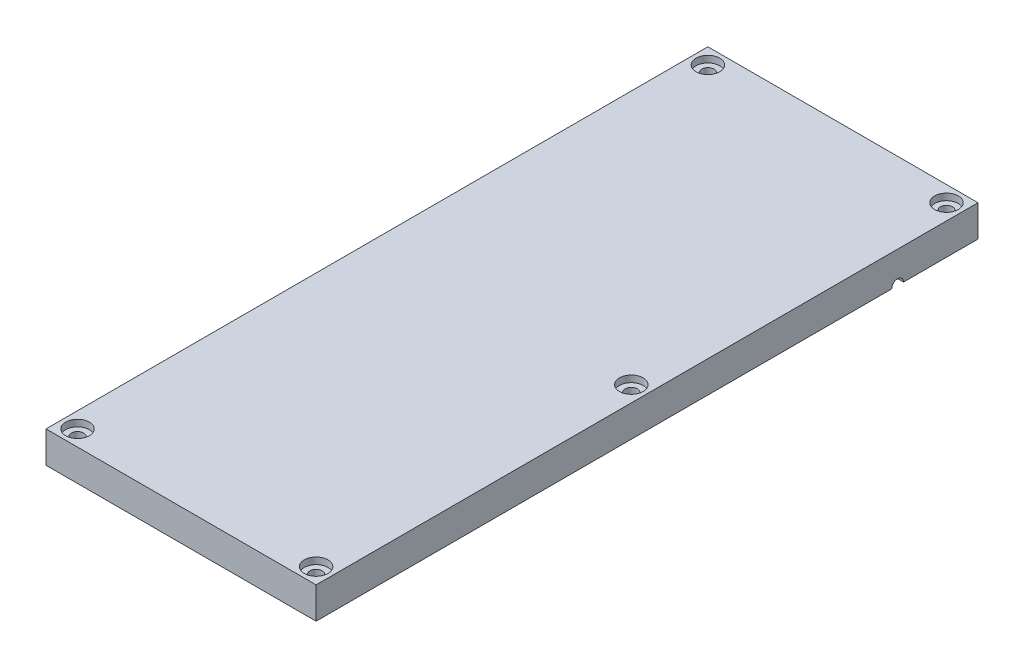
SolidWorks part; units mm, degrees
ref_plane "Front Plane" through (0, 0, 0) normal (0, 0, 1) x (1, 0, 0)
ref_plane "Top Plane" through (0, 0, 0) normal (0, 1, 0) x (1, 0, 0)
ref_plane "Right Plane" through (0, 0, 0) normal (1, 0, 0) x (0, 0, -1)
sketch "Sketch1" plane through (0, 0, 0) normal (0, 1, 0) x (1, 0, 0)
  line L1 (37.211, 0) -> (146.05, 0)
  line L2 (37.211, 0) -> (37.211, 266.7)
  line L3 (37.211, 266.7) -> (146.05, 266.7)
  line L4 (146.05, 0) -> (146.05, 266.7)
  dimension "D1" = 266.7
  dimension "D2" = 108.839
  dimension "D3" = 146.05
  dimension "D4" = 266.7
extrude "Boss-Extrude1" add sketch "Sketch1" along normal blind 12.7 from offset 12.7
hole_wizard "CBORE for #8 Binding Head Machine Screw1" positions "Sketch3" profile "Sketch2" counterbore size "#8" standard "ANSI Inch" end condition through all
sketch "Sketch3" plane through (0, 25.4, 0) normal (0, 1, 0) x (1, 0, 0)
  line L0 (146.05, 0) -> (146.05, 266.7) construction
  line L1 (37.211, 0) -> (146.05, 0) construction
  line L2 (146.05, 266.7) -> (37.211, 266.7) construction
  line L3 (37.211, 266.7) -> (37.211, 0) construction
  point P0 (139.7, 6.35)
  point P2 (139.7, 260.35)
  point P13 (43.561, 6.35)
  point P15 (43.561, 260.35)
  point P20 (139.7, 133.35)
  dimension "D1" = 6.35
  dimension "D2" = 6.35
  dimension "D3" = 6.35
  dimension "D4" = 6.35
  dimension "D5" = 6.35
  dimension "D6" = 6.35
  dimension "D7" = 6.35
  dimension "D8" = 6.35
  dimension "D9" = 6.35
  dimension "D10" = 133.35
sketch "Sketch2" plane through (139.7, 25.4, -6.35) normal (1, 0, 0) x (0, 0, 1)
  line L0 (0, 0) -> (0, 12.7)
  line L1 (0, 12.7) -> (2.4574, 12.7)
  line L3 (2.4574, 12.7) -> (2.4575, 2.667)
  line L4 (2.4575, 2.667) -> (4.7625, 2.667)
  line L5 (4.7625, 2.667) -> (4.7625, 0)
  line L7 (4.7625, 0) -> (0, 0)
  line L11 (0, -6.35) -> (0, 107.95) construction
  dimension "Thru Hole Dia." = 4.9149
  dimension "Thru Hole Depth" = 12.7
  dimension "C'Bore Dia." = 9.525
  dimension "C'Bore Depth" = 2.667
sketch "Sketch4" plane through (0, 12.7, 0) normal (0, -1, 0) x (-1, 0, 0)
  line L0 (-37.211, 266.7) -> (-37.211, 0) construction
  line L1 (-43.561, 18.415) -> (-114.935, 18.415)
  line L2 (-43.561, 18.415) -> (-43.561, 241.935)
  line L3 (-43.561, 241.935) -> (-114.935, 241.935)
  line L4 (-114.935, 18.415) -> (-114.935, 241.935)
  line L5 (-37.211, 0) -> (-146.05, 0) construction
  line L6 (-146.05, 266.7) -> (-37.211, 266.7) construction
  line L7 (-146.05, 0) -> (-146.05, 266.7) construction
  dimension "D1" = 6.35
  dimension "D2" = 18.415
  dimension "D3" = 24.765
  dimension "D4" = 31.115
extrude "Cut-Extrude1" cut sketch "Sketch4" against normal blind 9.525
sketch "Sketch5" plane through (0, 12.7, 0) normal (0, -1, 0) x (1, 0, 0)
  line L0 (114.935, -196.215) -> (120.015, -196.215)
  line L1 (114.935, -241.935) -> (114.935, -18.415) construction
  line L2 (120.015, -196.215) -> (120.015, -234.315)
  line L3 (120.015, -234.315) -> (128.905, -234.315)
  line L4 (128.905, -234.315) -> (128.905, -158.115)
  line L5 (128.905, -158.115) -> (137.795, -158.115)
  line L6 (137.795, -158.115) -> (137.795, -234.315)
  line L7 (137.795, -234.315) -> (146.05, -234.315)
  line L8 (146.05, 0) -> (146.05, -266.7) construction
  line L9 (114.935, -18.415) -> (43.561, -18.415) construction
  dimension "D1" = 38.1
  dimension "D2" = 76.2
  dimension "D3" = 76.2
  dimension "D4" = 5.08
  dimension "D5" = 8.89
  dimension "D6" = 8.89
  dimension "D7" = 177.8
sketch "Sketch6" plane through (146.05, 0, 0) normal (1, 0, 0) x (0, 0, -1)
  line L0 (234.315, 12.7) -> (158.115, 12.7) construction
  line L1 (196.215, 12.7) -> (234.315, 12.7) construction
  circle A0 centre (234.315, 12.7) radius 2.3813
  dimension "D1" = 4.7625
  dimension "D2" = 0
sweep "Cut-Sweep1" cut profiles "Sketch6" path "Sketch5"
sketch "Sketch8" plane through (0, 12.7, 0) normal (0, -1, 0) x (1, 0, 0)
  line L0 (114.935, -193.8337) -> (114.935, -18.415) construction
  line L1 (114.935, -56.515) -> (127.635, -56.515)
  line L2 (114.935, -56.515) -> (114.935, -69.215)
  line L3 (114.935, -69.215) -> (127.635, -69.215)
  line L4 (127.635, -56.515) -> (127.635, -69.215)
  line L5 (43.561, -241.935) -> (114.935, -241.935) construction
  line L6 (83.185, -241.935) -> (95.885, -241.935)
  line L7 (83.185, -241.935) -> (83.185, -254.635)
  line L8 (83.185, -254.635) -> (95.885, -254.635)
  line L9 (95.885, -241.935) -> (95.885, -254.635)
  line L10 (114.935, -241.935) -> (114.935, -18.415) construction
  line L11 (114.935, -18.415) -> (43.561, -18.415) construction
  dimension "D1" = 12.7
  dimension "D2" = 12.7
  dimension "D3" = 12.7
  dimension "D4" = 12.7
  dimension "D5" = 19.05
  dimension "D6" = 38.1
extrude "Cut-Extrude3" cut sketch "Sketch8" against normal blind 9.525
